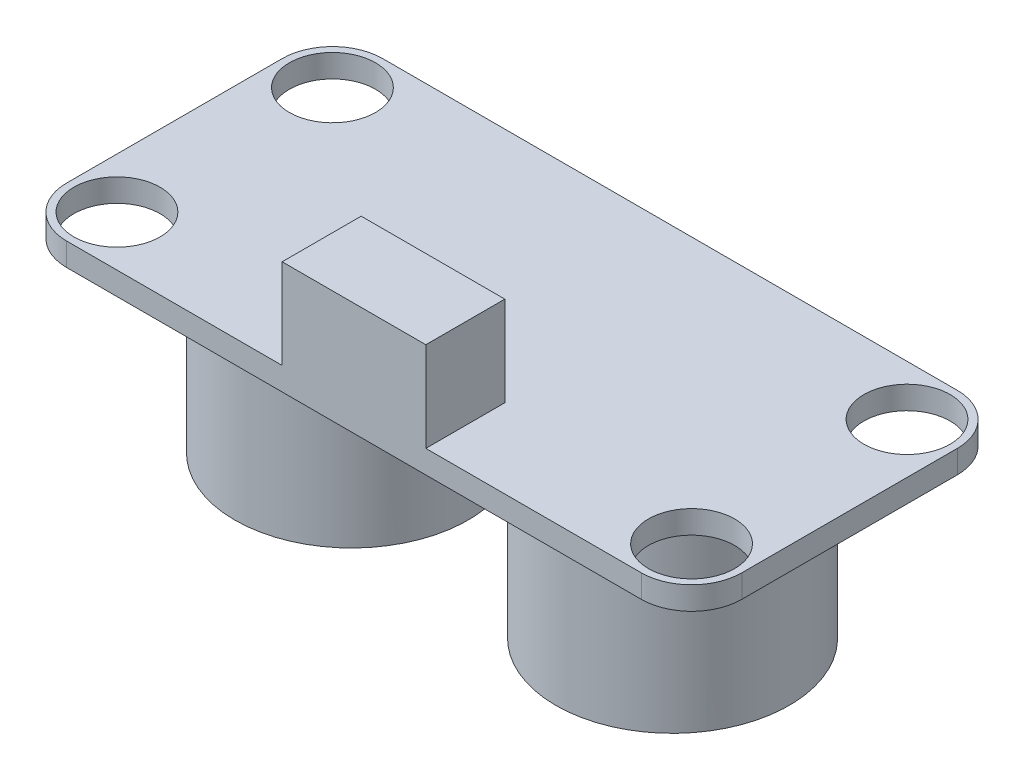
SolidWorks part; units mm, degrees
ref_plane "Front Plane" through (0, 0, 0) normal (0, 0, 1) x (1, 0, 0)
ref_plane "Top Plane" through (0, 0, 0) normal (0, 1, 0) x (1, 0, 0)
ref_plane "Right Plane" through (0, 0, 0) normal (1, 0, 0) x (0, 0, -1)
sketch "Sketch1" plane through (0, 0, 0) normal (0, 1, 0) x (1, 0, 0)
  line L0 (3.5, 0) -> (43.5, 0)
  line L1 (47, 3.5) -> (47, 18.5)
  line L2 (43.5, 22) -> (3.5, 22)
  line L3 (0, 18.5) -> (0, 3.5)
  arc A0 (47, 18.5) -> (43.5, 22) centre (43.5, 18.5) ccw
  arc A1 (43.5, 0) -> (47, 3.5) centre (43.5, 3.5) ccw
  arc A2 (3.5, 0) -> (0, 3.5) centre (3.5, 3.5) cw
  arc A3 (3.5, 22) -> (0, 18.5) centre (3.5, 18.5) ccw
  circle A4 centre (3.5, 18.5) radius 3
  circle A5 centre (3.5, 3.5) radius 3
  circle A6 centre (43.5, 3.5) radius 3
  circle A7 centre (43.5, 18.5) radius 3
  point P11 (0, 0)
  dimension "D1" = 3.5
  dimension "D2" = 22
  dimension "D3" = 47
extrude "Boss-Extrude1" add sketch "Sketch1" along normal blind 1.6
sketch "Sketch2" plane through (0, 1.6, 0) normal (0, 1, 0) x (1, 0, 0)
  line L0 (18.5, 0) -> (28.5, 0)
  line L1 (3.5, 0) -> (43.5, 0) construction
  line L2 (28.5, 0) -> (28.5, 5.5)
  line L3 (28.5, 5.5) -> (18.5, 5.5)
  line L4 (18.5, 5.5) -> (18.5, 0)
  line L5 (47, 3.5) -> (47, 18.5) construction
  point P4 (23.5, 0)
  dimension "D1" = 10
  dimension "D2" = 5.5
  dimension "D3" = 23.5
extrude "Boss-Extrude2" add sketch "Sketch2" along normal blind 6.25
sketch "Sketch3" plane through (0, 0, 0) normal (0, -1, 0) x (-1, 0, 0)
  line L0 (0, 18.5) -> (0, 3.5) construction
  line L1 (-47, 3.5) -> (-47, 18.5) construction
  line L2 (-3.5, 0) -> (-43.5, 0) construction
  circle A0 centre (-12.325, 11) radius 8.125
  circle A1 centre (-34.675, 11) radius 8.125
  dimension "D3" = 16.25
  dimension "D4" = 16.25
  dimension "D1" = 12.325
  dimension "D2" = 12.325
  dimension "D5" = 11
  dimension "D6" = 11
extrude "Boss-Extrude3" add sketch "Sketch3" along normal blind 12.25
